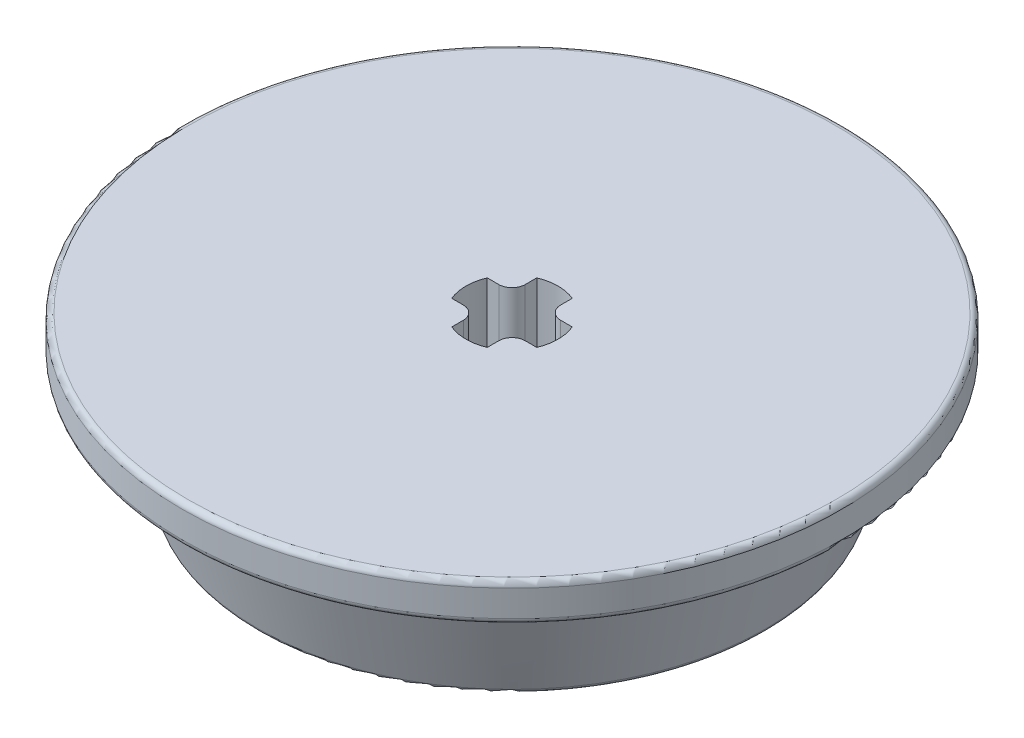
SolidWorks part; units mm, degrees
ref_plane "Front Plane" through (0, 0, 0) normal (0, 0, 1) x (1, 0, 0)
ref_plane "Top Plane" through (0, 0, 0) normal (0, 1, 0) x (1, 0, 0)
ref_plane "Right Plane" through (0, 0, 0) normal (1, 0, 0) x (0, 0, -1)
sketch "Sketch1" plane through (0, 0, 0) normal (0, 1, 0) x (1, 0, 0)
  line L2 (0, 0) -> (0, 47.5777) construction
  line L3 (0, 0) -> (50000, 0) construction
  line L6 (-0.89, 0.89) -> (0, 0) construction
  line L7 (0, 0) -> (0.89, 0.89) construction
  line L12 (2.39, 0) -> (2.39, 3.5727) construction
  line L13 (0, 2.39) -> (50000, 2.39) construction
  line L14 (-2.39, 0.4111) -> (-2.39, -49999.5889) construction
  line L15 (0.2318, -2.39) -> (-49999.7682, -2.39) construction
  line L16 (0, 0) -> (-0.89, -0.89) construction
  line L17 (0, 0) -> (0.89, -0.89) construction
  line L18 (-0.94, 0.94) -> (-2.2517, 0.94)
  line L19 (-2.2517, -0.94) -> (-0.94, -0.94)
  line L20 (-0.94, -0.94) -> (-0.94, -2.2517)
  line L21 (0.94, -2.2517) -> (0.94, -0.94)
  line L22 (0.94, -0.94) -> (2.2517, -0.94)
  line L23 (0.94, 0.94) -> (2.2517, 0.94)
  line L24 (0.94, 2.2517) -> (0.94, 0.94)
  line L25 (-0.94, 2.2517) -> (-0.94, 0.94)
  arc A4 (-2.2517, 0.94) -> (-2.2517, -0.94) centre (0, 0) ccw
  arc A5 (-0.94, -2.2517) -> (0.94, -2.2517) centre (0, 0) ccw
  arc A6 (2.2517, 0.94) -> (2.2517, -0.94) centre (0, 0) cw
  arc A7 (-0.94, 2.2517) -> (0.94, 2.2517) centre (0, 0) cw
  point P15 (0, 2.39)
  point P24 (2.39, 0)
  point P29 (-2.39, 0)
  point P30 (0, -2.39)
  line B0 (-0.89, 2.2181) -> (-0.89, 0.89) construction
  line B1 (-0.89, 0.89) -> (-2.2181, 0.89) construction
  line B2 (0.89, 2.2181) -> (0.89, 0.89) construction
  line B3 (0.89, 0.89) -> (2.2181, 0.89) construction
  line B4 (-2.2181, -0.89) -> (-0.89, -0.89) construction
  line B5 (-0.89, -0.89) -> (-0.89, -2.2181) construction
  line B6 (0.89, -2.2181) -> (0.89, -0.89) construction
  line B7 (0.89, -0.89) -> (2.2181, -0.89) construction
  arc B8 (-0.89, 2.2181) -> (0.89, 2.2181) centre (0, 0) cw construction
  arc B9 (-2.2181, 0.89) -> (-2.2181, -0.89) centre (0, 0) ccw construction
  arc B10 (2.2181, 0.89) -> (2.2181, -0.89) centre (0, 0) cw construction
  arc B11 (-0.89, -2.2181) -> (0.89, -2.2181) centre (0, 0) ccw construction
sketch_block_instance "Lego Axle - Unfilleted-1"
sketch_block "Lego Axle - Unfilleted" parameters "D1"=10.5762, "D2"=12.3972, "D3"=62.5785, "D4"=1.2287, "D5"=12.9019, "D6"=1.0841, "D7"=0.05
sketch "Sketch2" plane through (0, 0, 0) normal (0, 0, 1) x (1, 0, 0)
  line L0 (0, 0) -> (17.4605, 0)
  line L1 (200000.2318, 0) -> (-249999.7682, 0) construction
  line L2 (17.4605, 0) -> (17.4605, -2)
  line L3 (17.4605, -2) -> (15, -2)
  line L4 (15, -2) -> (13.3923, -8)
  line L5 (13.3923, -8) -> (0, -8)
  line L6 (0, -8) -> (0, 0)
  line L7 (0, 0) -> (0, 50000) construction
  dimension "D1" = 30
  dimension "D2" = 15
  dimension "D3" = 8
  dimension "D4" = 2
revolve "Revolve1" add sketch "Sketch2" angle 360 about L7
extrude "Cut-Extrude1" cut sketch "Sketch1" against normal through all
fillet "Fillet1" radius 0.7 4 edges at (-0.94, -4, 0.94) (0.94, -4, 0.94) (0.94, -4, -0.94) (-0.94, -4, -0.94)
fillet "Fillet2" radius 0.3 4 edges at (0, -8, -13.3923) (0, 0, -17.4605) (0, -2, -15) (0, -2, -17.4605)
